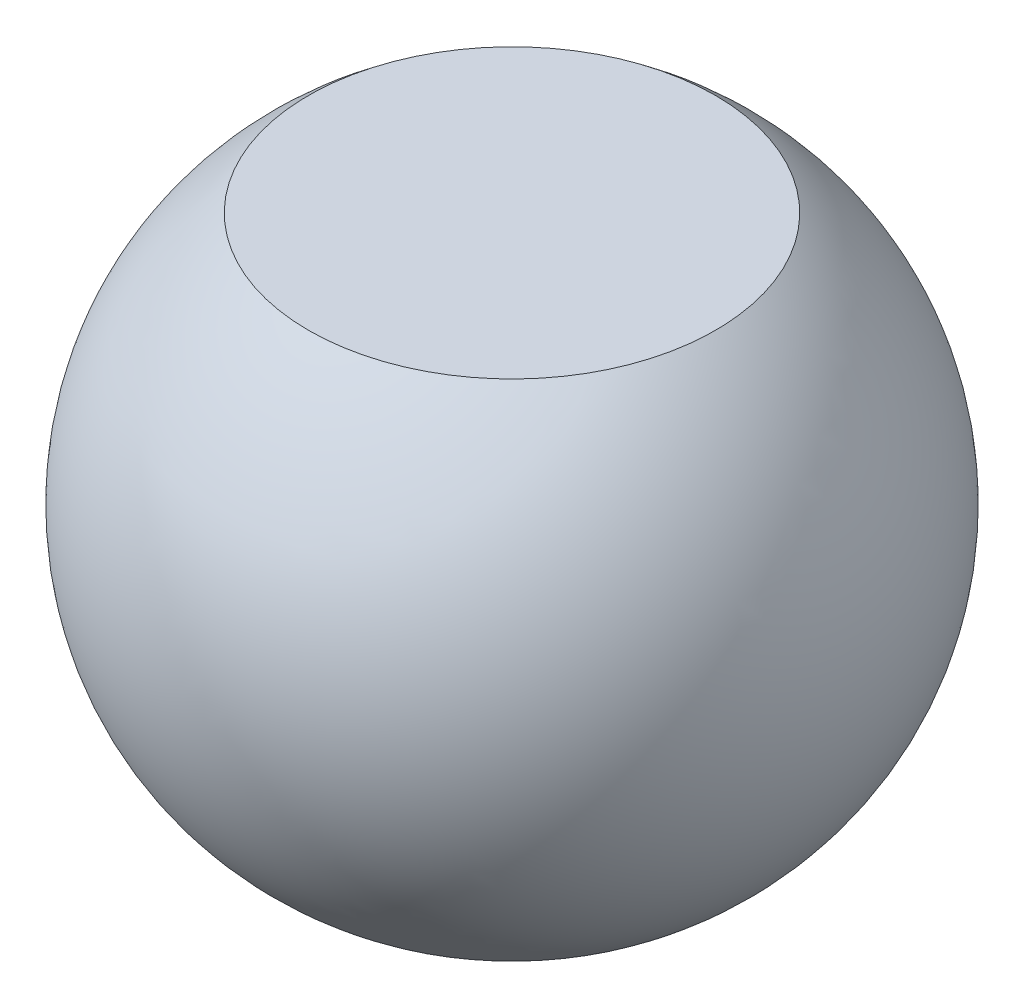
SolidWorks part; units mm, degrees
ref_plane "Front Plane" through (0, 0, 0) normal (0, 0, 1) x (1, 0, 0)
ref_plane "Top Plane" through (0, 0, 0) normal (0, 1, 0) x (1, 0, 0)
ref_plane "Right Plane" through (0, 0, 0) normal (1, 0, 0) x (0, 0, -1)
sketch "Sketch2" plane through (0, 0, 0) normal (1, 0, 0) x (0, 0, -1)
  line L0 (0, 0) -> (0, 805) construction
  line L1 (0, 0) -> (323, 0) construction
  line L2 (323, 0) -> (0, 0)
  line L3 (0, 805) -> (324.4168, 805)
  line L4 (0, 0) -> (0, 805)
  arc A0 (323, 0) -> (324.4168, 805) centre (23.7135, 403.028) ccw
  dimension "D3" = 502
  dimension "D1" = 323
  dimension "D2" = 805
revolve "Revolve1" add sketch "Sketch2" angle 360 about L4
sketch "Sketch3" plane through (0, 0, 0) normal (0, 0, 1) x (1, 0, 0)
  line L0 (-893, 784) -> (-745.515, 820.7721)
  line L1 (-893, 784) -> (-703.8317, 784) construction
  line L2 (-124.0567, 112.3589) -> (-741.9433, 112.3589) construction
  line L3 (-535.9692, 694.9822) -> (-1250.0308, 873.0178) construction
  line L4 (-71.2089, 479.0122) -> (-933.1057, 630.9878) construction
  line L5 (-450.0948, 525.3518) -> (-1040.9353, 1116.1924) construction
  arc A0 (-502.1573, 555) -> (-433, 112.3589) centre (-23.7135, 403.028) ccw
  arc A1 (-324.4168, 805) -> (-323, 0) centre (-23.7135, 403.028) ccw construction
  spline S0 degree 3 poles (-893, 784) (-661.7462, 726.3419) (-757, 112.3589) (-433, 112.3589) knots 0 0 0 0 1 1 1 1
  spline S1 degree 3 poles (-745.515, 820.7721) (-647.0416, 722.2987) (-645.8068, 580.3293) (-502.1573, 555) knots 0 0 0 0 1 1 1 1
  dimension "D7" = 972
  dimension "D8" = 14
  dimension "D9" = 715
  dimension "D10" = 10
  dimension "D11" = 45
  dimension "D1" = 433
  dimension "D2" = 555
  dimension "D3" = 152
  dimension "D4" = 14
  dimension "D5" = 784
  dimension "D6" = 893
ref_plane "Plane1" through (-405.5458, -63.3616, 0) normal (0.988, 0.1544, 0) x (0, 0, -1)
